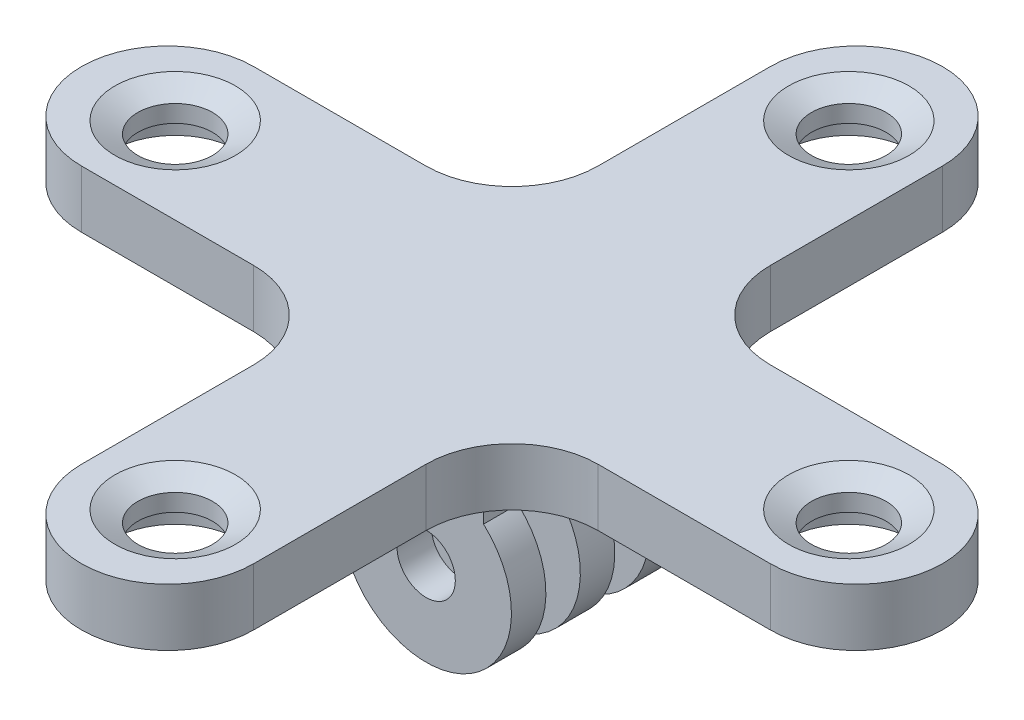
SolidWorks part; units mm, degrees
ref_plane "Piano frontale" through (0, 0, 0) normal (0, 0, 1) x (1, 0, 0)
ref_plane "Piano superiore" through (0, 0, 0) normal (0, 1, 0) x (1, 0, 0)
ref_plane "Piano destro" through (0, 0, 0) normal (1, 0, 0) x (0, 0, -1)
sketch "Schizzo3" plane through (0, 0, 0) normal (0, 1, 0) x (1, 0, 0)
  line L0 (-33.4642, 18.101) -> (-3.4642, 48.101) construction
  line L1 (-33.4642, 3.101) -> (-33.4642, 18.101) construction
  line L2 (-33.4642, 3.101) -> (41.5358, 3.101) construction
  line L3 (41.5358, 3.101) -> (41.5358, 18.101) construction
  line L4 (-33.4642, 18.101) -> (41.5358, 18.101) construction
  line L5 (-3.4642, -26.899) -> (-3.4642, 48.101) construction
  line L6 (-3.4642, -26.899) -> (11.5358, -26.899) construction
  line L7 (11.5358, -26.899) -> (11.5358, 48.101) construction
  line L8 (-3.4642, 48.101) -> (11.5358, 48.101) construction
  line L9 (11.5358, 48.101) -> (41.5358, 18.101) construction
  line L10 (41.5358, 3.101) -> (11.5358, -26.899) construction
  line L11 (-3.4642, -26.899) -> (-33.4642, 3.101) construction
  line L12 (-33.4642, 10.601) -> (41.5358, 10.601) construction
  line L13 (-33.4642, 3.101) -> (-33.4642, 18.101) construction
  line L14 (-33.4642, 3.101) -> (-25.9642, 3.101) construction
  line L15 (-25.9642, 3.101) -> (-25.9642, 18.101) construction
  line L16 (-33.4642, 18.101) -> (-25.9642, 18.101) construction
  line L17 (4.0358, 48.101) -> (4.0358, -26.899) construction
  line L18 (-3.4642, 40.601) -> (11.5358, 40.601) construction
  line L19 (34.0358, 18.101) -> (34.0358, 3.101) construction
  line L20 (11.5358, -19.399) -> (-3.4642, -19.399) construction
  line L21 (-33.4642, 18.101) -> (-3.4642, 18.101) construction
  line L22 (-33.4642, 3.101) -> (-3.4642, 3.101) construction
  line L23 (41.5358, 3.101) -> (11.5358, 3.101) construction
  line L24 (41.5358, 18.101) -> (11.5358, 18.101) construction
  line L25 (11.5358, 25.601) -> (19.0358, 25.601) construction
  line L26 (-3.4642, 18.101) -> (-3.4642, 25.601) construction
  line L27 (-3.4642, 18.101) -> (-10.9642, 18.101) construction
  line L28 (-10.9642, 18.101) -> (-10.9642, 25.601) construction
  line L29 (-3.4642, 25.601) -> (-10.9642, 25.601) construction
  line L30 (19.0358, 18.101) -> (19.0358, 25.601) construction
  line L31 (19.0358, 3.101) -> (19.0358, -4.399) construction
  line L32 (11.5358, -4.399) -> (19.0358, -4.399) construction
  line L33 (-3.4642, -4.399) -> (-10.9642, -4.399) construction
  line L34 (-10.9642, 3.101) -> (-10.9642, -4.399) construction
  line L35 (-25.9642, 18.101) -> (-10.9642, 18.101)
  line L36 (-3.4642, 25.601) -> (-3.4642, 40.601)
  line L37 (11.5358, 40.601) -> (11.5358, 25.601)
  line L38 (-68.7263, -41.079) -> (85.3632, -41.079) construction
  line L39 (19.0358, 18.101) -> (34.0358, 18.101)
  line L40 (34.0358, 3.101) -> (19.0358, 3.101)
  line L41 (11.5358, -4.399) -> (11.5358, -19.399)
  line L42 (-3.4642, -19.399) -> (-3.4642, -4.399)
  line L44 (-10.9642, 3.101) -> (-25.9642, 3.101)
  arc A0 (-25.9642, 3.101) -> (-25.9642, 18.101) centre (-25.9642, 10.601) cw
  arc A1 (-10.9642, 18.101) -> (-3.4642, 25.601) centre (-10.9642, 25.601) ccw
  arc A2 (-3.4642, 40.601) -> (11.5358, 40.601) centre (4.0358, 40.601) cw
  arc A3 (11.5358, 25.601) -> (19.0358, 18.101) centre (19.0358, 25.601) ccw
  arc A4 (34.0358, 18.101) -> (34.0358, 3.101) centre (34.0358, 10.601) cw
  arc A5 (19.0358, 3.101) -> (11.5358, -4.399) centre (19.0358, -4.399) ccw
  arc A6 (11.5358, -19.399) -> (-3.4642, -19.399) centre (4.0358, -19.399) cw
  arc A7 (-3.4642, -4.399) -> (-10.9642, 3.101) centre (-10.9642, -4.399) ccw
  point P23 (4.0358, 10.601)
  point P40 (4.0358, 10.601)
  point P61 (4.0358, 10.601)
  dimension "D1" = 75
  dimension "D2" = 15
  dimension "D3" = 7.5
  dimension "D5" = 7.5
  dimension "D6" = 7.5
  dimension "D4" = 4
  dimension "D7" = 4
  dimension "D8" = 4
extrude "Estrusione-Estrusione1" add sketch "Schizzo3" along normal blind 5
sketch "Schizzo4" plane through (0, 5, 0) normal (0, 1, 0) x (1, 0, 0)
  line L0 (4.0358, -26.899) -> (4.0358, 48.101) construction
  line L1 (-33.4642, 10.601) -> (41.5358, 10.601) construction
  line L2 (-25.2992, 10.601) -> (4.0358, 39.936) construction
  line L3 (4.0358, 39.936) -> (33.3708, 10.601) construction
  line L4 (33.3708, 10.601) -> (4.0358, -18.734) construction
  line L5 (4.0358, -18.734) -> (-25.2992, 10.601) construction
  circle A4 centre (4.0358, -18.734) radius 3.25
  circle A5 centre (4.0358, 39.936) radius 3.25
  circle A6 centre (-25.2992, 10.601) radius 3.25
  circle A7 centre (33.3708, 10.601) radius 3.25
  dimension "D1" = 6.5
  dimension "D2" = 58.67
  dimension "D3" = 58.67
extrude "Taglio-Estrusione1" cut sketch "Schizzo4" against normal through all
chamfer "Smusso2" distance 2 distance2 1 4 edges at (-25.2992, 5, -7.351) (33.3708, 5, -7.351) (4.0358, 5, 21.984) (4.0358, 5, -36.686)
sketch "Schizzo5" plane through (0, 0, 0) normal (0, -1, 0) x (1, 0, 0)
  line L0 (-22.4807, 15.9155) -> (30.5523, -37.1175) construction
  line L1 (-22.4807, -37.1175) -> (28.0435, 13.4067) construction
  circle A0 centre (4.0366, 18.7336) radius 5.5
  circle A1 centre (4.0366, -39.9364) radius 5.5
  circle A2 centre (-25.2984, -10.6014) radius 5.5
  circle A3 centre (33.3704, -10.6002) radius 5.5
  dimension "D1" = 11
extrude "Taglio-Estrusione2" cut sketch "Schizzo5" against normal blind 2.5
sketch "Schizzo7" plane through (0, 0, 0) normal (0, 0, 1) x (1, 0, 0)
  line L0 (11.4885, 0) -> (-3.3715, 0) construction
  line L1 (-3.3715, 0) -> (-3.3715, -17.43) construction
  line L2 (-3.3715, -17.43) -> (11.4885, -17.43) construction
  line L3 (11.4885, -17.43) -> (11.4885, 0) construction
  line L5 (19.0358, 0) -> (34.0358, 0) construction
  line L6 (-0.9415, -4.5041) -> (9.0585, -4.5041) construction
  line L7 (-0.9415, -4.5041) -> (-0.9415, 0)
  line L8 (-0.9415, 0) -> (9.0585, 0)
  line L9 (9.0585, 0) -> (9.0585, -4.5041)
  line L10 (4.0585, 0) -> (4.0585, -10) construction
  line L13 (-4.9403, 0) -> (13.0585, 0) construction
  circle A0 centre (4.0585, -10) radius 2.54
  arc A1 (-0.9415, -4.5041) -> (9.0585, -4.5041) centre (4.0585, -10) ccw
  dimension "D5" = 7.43
  dimension "D6" = 5.08
  dimension "D1" = 10
  dimension "D2" = 14.86
  dimension "D3" = 10
  dimension "D4" = 7.43
  dimension "D7" = 9
  dimension "D8" = 17.9988
extrude "Estrusione-Estrusione2" add sketch "Schizzo7" against normal blind 20
sketch "Schizzo9" plane through (0, 0, 0) normal (0, -1, 0) x (1, 0, 0)
  line L0 (-33.4642, -10.601) -> (41.5358, -10.601) construction
  line L1 (4.0358, 26.899) -> (4.0358, -48.101) construction
  line L2 (-5.8909, -6.101) -> (-5.8909, -9.101)
  line L3 (14.1091, -9.101) -> (-5.8909, -9.101)
  line L4 (14.1091, -9.101) -> (14.1091, -12.101) construction
  line L5 (14.1091, -12.101) -> (-5.8909, -12.101)
  line L6 (-5.8909, -9.101) -> (-5.8909, -12.101) construction
  line L7 (14.1091, -3.101) -> (-5.8909, -3.101)
  line L8 (14.1091, -3.101) -> (14.1091, -6.101) construction
  line L9 (14.1091, -6.101) -> (-5.8909, -6.101)
  line L10 (-5.8909, -3.101) -> (-5.8909, -6.101) construction
  line L11 (14.1091, -15.101) -> (-5.8909, -15.101)
  line L12 (14.1091, -15.101) -> (14.1091, -18.101) construction
  line L13 (14.1091, -18.101) -> (-5.8909, -18.101)
  line L14 (-5.8909, -15.101) -> (-5.8909, -18.101) construction
  line L15 (-5.8909, -12.101) -> (-5.8909, -15.101)
  line L16 (14.1091, -15.101) -> (14.1091, -12.101)
  line L17 (14.1091, -9.101) -> (14.1091, -6.101)
  line L18 (4.0358, -10.601) -> (4.0358, -25.3514) construction
  line L19 (-5.8909, -3.101) -> (-5.8909, 1.6118)
  line L20 (-5.8909, 1.6118) -> (14.1091, 1.6118)
  line L21 (14.1091, 1.6118) -> (14.1091, -3.101)
  line L22 (14.1091, -18.101) -> (14.1091, -22.2466)
  line L23 (14.1091, -22.2466) -> (-5.8909, -22.2466)
  line L24 (-5.8909, -22.2466) -> (-5.8909, -18.101)
  arc A0 (-25.9642, -3.101) -> (-25.9642, -18.101) centre (-25.9642, -10.601) ccw construction
  arc A1 (34.0358, -18.101) -> (34.0358, -3.101) centre (34.0358, -10.601) ccw construction
  arc A2 (11.5358, 19.399) -> (-3.4642, 19.399) centre (4.0358, 19.399) ccw construction
  arc A3 (-3.4642, -40.601) -> (11.5358, -40.601) centre (4.0358, -40.601) ccw construction
  dimension "D1" = 3
  dimension "D2" = 20
  dimension "D3" = 3
  dimension "D4" = 1.5
extrude "Taglio-Estrusione3" cut sketch "Schizzo9" along normal blind 20
